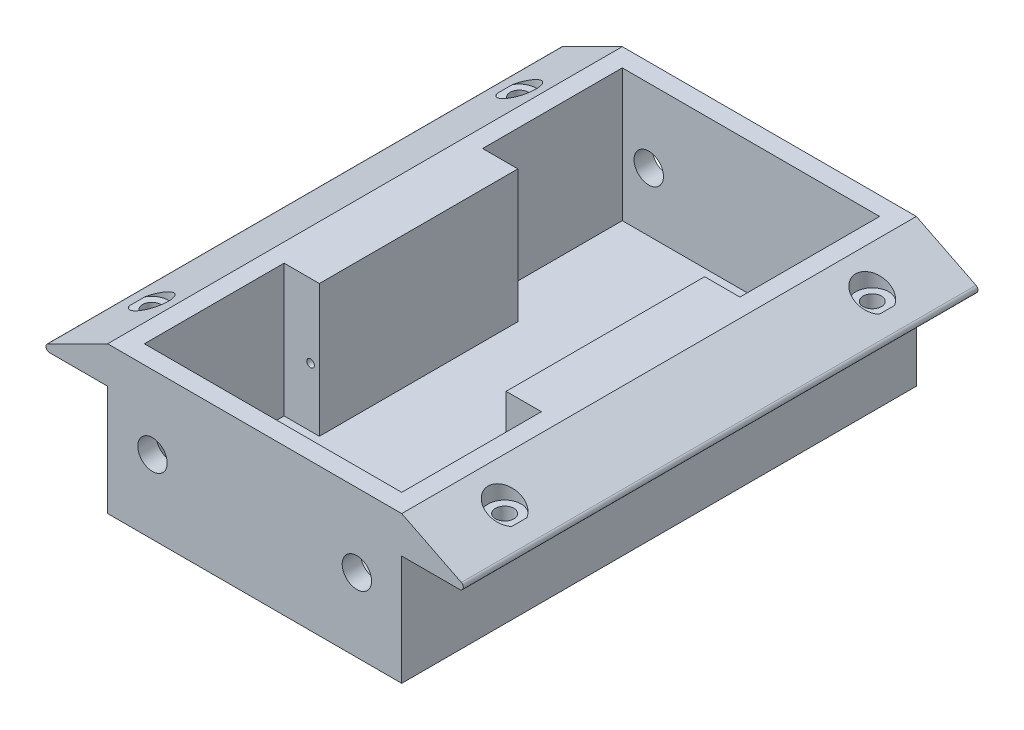
SolidWorks part; units mm, degrees
ref_plane "Front Plane" through (0, 0, 0) normal (0, 0, 1) x (1, 0, 0)
ref_plane "Top Plane" through (0, 0, 0) normal (0, 1, 0) x (1, 0, 0)
ref_plane "Right Plane" through (0, 0, 0) normal (1, 0, 0) x (0, 0, -1)
other "Center of Mass"
sketch "Sketch1" plane through (0, 0, 0) normal (0, 0, 1) x (1, 0, 0)
  line L0 (0, 0) -> (-25.0161, 0) construction
  line L5 (-60, 5) -> (-60, -5) construction
  line L6 (60, 5) -> (60, -5) construction
  line L11 (-20, 10) -> (-30, 5)
  line L13 (0, 0) -> (0, -23.6771) construction
  line L14 (-69.28, 5) -> (69.28, 5) construction
  line L15 (-69.28, 5) -> (-69.28, -5) construction
  line L16 (-69.28, -5) -> (69.28, -5) construction
  line L17 (69.28, 5) -> (69.28, -5) construction
  line L18 (-69.28, 5) -> (69.28, -5) construction
  line L19 (-69.28, -5) -> (69.28, 5) construction
  line L20 (16.1, 6.1) -> (-16.1, 6.1) construction
  line L21 (16.1, 6.1) -> (16.1, -6.1) construction
  line L22 (16.1, -6.1) -> (-16.1, -6.1) construction
  line L23 (-16.1, 6.1) -> (-16.1, -6.1) construction
  line L24 (16.1, 6.1) -> (-16.1, -6.1) construction
  line L25 (16.1, -6.1) -> (-16.1, 6.1) construction
  line L26 (-20, 10) -> (20, 10)
  line L27 (-20, 10) -> (-20, -10)
  line L28 (-20, -10) -> (20, -10)
  line L29 (20, 10) -> (20, -10)
  line L30 (-20, 10) -> (20, -10) construction
  line L31 (-20, -10) -> (20, 10) construction
  line L32 (-30, 5) -> (-20, 5)
  line L33 (-20, 5) -> (-20, 10)
  line L35 (20, 10) -> (30, 5)
  line L36 (30, 5) -> (20, 5)
  line L38 (20, 10) -> (20, 5)
  circle A0 centre (-13.95, 0) radius 2 construction
  circle A1 centre (13.95, 0) radius 2 construction
  point P4 (0, 0)
  point P14 (0, 0)
  point P20 (0, 0)
  point P23 (0, 0)
  dimension "D5" = 32.2
  dimension "D9" = 20
  dimension "D13" = 10
  dimension "D14" = 10
  dimension "D6" = 4
  dimension "D2" = 120
  dimension "D3" = 60
  dimension "D4" = 12.2
  dimension "D7" = 2.15
  dimension "D8" = 2.15
  dimension "D10" = 40
  dimension "D11" = 10
  dimension "D12" = 138.56
extrude "Boss-Extrude1" add sketch "Sketch1" along normal mid plane 70 contours L29 L26 L27 L28 A1 A0 | L11 L32 L27 | L36 L35 L29
sketch "Sketch2" plane through (0, 10, 0) normal (0, 1, 0) x (1, 0, 0)
  line L0 (-20, -35) -> (20, -35) construction
  line L2 (-20, 35) -> (20, 35) construction
  line L3 (-20, -35) -> (-20, 35) construction
  line L4 (-20, -35) -> (20, -35) construction
  line L6 (-20, 35) -> (20, 35) construction
  line L7 (-20, -35) -> (-20, 35) construction
  line L23 (-17.5, -13.5) -> (-17.5, -32.5)
  line L32 (-17.5, 13.5) -> (-12.7, 13.5)
  line L36 (-17.5, -13.5) -> (-12.7, -13.5)
  line L37 (17.5, 32.5) -> (-17.5, 32.5)
  line L38 (-17.5, 32.5) -> (-17.5, -32.5)
  line L39 (-17.5, -32.5) -> (17.5, -32.5)
  line L40 (17.5, -32.5) -> (17.5, 32.5)
  line L41 (17.5, 32.5) -> (-17.5, 32.5)
  line L42 (-17.5, 32.5) -> (-17.5, 13.5)
  line L43 (-17.5, -32.5) -> (17.5, -32.5)
  line L44 (17.5, -32.5) -> (17.5, -13.5)
  line L45 (-12.7, 13.5) -> (-12.7, -13.5)
  line L46 (-17.5, 13.5) -> (-12.7, -13.5) construction
  line L47 (-17.5, -13.5) -> (-12.7, 13.5) construction
  line L48 (12.7, 13.5) -> (17.5, 13.5)
  line L49 (12.7, 13.5) -> (12.7, -13.5)
  line L50 (12.7, -13.5) -> (17.5, -13.5)
  line L52 (12.7, 13.5) -> (17.5, -13.5) construction
  line L53 (12.7, -13.5) -> (17.5, 13.5) construction
  line L54 (17.5, 13.5) -> (17.5, 32.5)
  point P2 (-15.1, 0)
  point P9 (15.1, 0)
  point P18 (0, 0)
  dimension "D2" = 19
  dimension "D3" = 4.8
  dimension "D1" = 2.5
extrude "Cut-Extrude1" cut sketch "Sketch2" against normal blind 18
sketch "Sketch3" plane through (0, 10, 0) normal (0, 1, 0) x (1, 0, 0)
  circle A0 centre (-24, 25) radius 1.25
  circle A1 centre (-24, -25) radius 1.25
  circle A2 centre (24, 25) radius 1.25
  circle A3 centre (24, -25) radius 1.25
  point P8 (0, 0)
  point P11 (-29.5989, 19.9752)
  point P14 (-23.4931, 20.5683)
  dimension "D1" = 2.5
  dimension "D4" = 25
  dimension "D2" = 24
  dimension "D3" = 24
  dimension "D5" = 25
extrude "Cut-Extrude2" cut sketch "Sketch3" against normal through all
sketch "Sketch5" plane through (0, 0, 0) normal (0, 0, -1) x (-1, 0, 0)
  circle A0 centre (-13.9, 0) radius 0.5184
  circle A1 centre (13.9, 0) radius 0.5184
  point P6 (0, 0)
  point P7 (0, 0)
  point P8 (-13.9, 0)
  line B0 (-16.05, -6.1) -> (-16.05, 6.1)
  line B1 (-16.05, -6.1) -> (16.05, -6.1)
  line B2 (16.05, -6.1) -> (16.05, 6.1)
  line B3 (-16.05, 6.1) -> (16.05, 6.1)
  line B4 (-16.05, -6.1) -> (16.05, 6.1) construction
  line B5 (16.05, -6.1) -> (-16.05, 6.1) construction
  circle B6 centre (5.15, 0) radius 2.5
  circle B7 centre (13.9, 0) radius 1.1
  circle B8 centre (-13.9, 0) radius 1.1
  dimension "D1" = 1.0367
sketch_block_instance "sg90Servo-1"
sketch_block "Block1" parameters "D3"=1.8404, "D4"=1.7531, "D5"=2.2, "D6"=5, "D1"=12.2, "D2"=32.1, "D7"=2.347
extrude "Cut-Extrude5" cut sketch "Sketch5" against normal mid plane 60 contours A0 | A1
fillet "Fillet2" radius 0.5 2 edges at (30, 5, 0) (-30, 5, 0)
sketch "Sketch7" plane through (0, 10, 0) normal (0, 1, 0) x (1, 0, 0)
  circle A19 centre (-24, 25) radius 2.25
  circle A20 centre (-24, 25) radius 2.25
  circle A22 centre (24, 25) radius 2.25
  circle A23 centre (24, 25) radius 2.25
  circle A25 centre (-24, -25) radius 2.25
  circle A26 centre (-24, -25) radius 2.25
  circle A28 centre (24, -25) radius 2.25
  circle A29 centre (24, -25) radius 2.25
  dimension "D1" = 1
  dimension "D2" = 1
  dimension "D3" = 1
  dimension "D4" = 1
extrude "Cut-Extrude6" cut sketch "Sketch7" against normal blind 3
sketch "Sketch8" plane through (0, 0, 35) normal (0, 0, 1) x (1, 0, 0)
  circle A0 centre (-13.9, 0) radius 2
  circle A1 centre (13.9, 0) radius 2
  circle A2 centre (13.9, 0) radius 0.5184 construction
  circle A3 centre (-13.9, 0) radius 0.5184 construction
  circle A4 centre (13.9, 0) radius 0.5184 construction
  circle A5 centre (-13.9, 0) radius 0.5184 construction
  point P10 (0, 0)
  dimension "D1" = 4
extrude "Cut-Extrude7" cut sketch "Sketch8" against normal up to vertex (2.5 mm away)
sketch "Sketch9" plane through (0, 0, -35) normal (0, 0, -1) x (-1, 0, 0)
  circle A2 centre (13.9, 0) radius 2 construction
  circle A3 centre (-13.9, 0) radius 2 construction
  circle A4 centre (13.9, 0) radius 2
  circle A5 centre (-13.9, 0) radius 2
extrude "Cut-Extrude8" cut sketch "Sketch9" against normal up to vertex (2.5 mm away)
